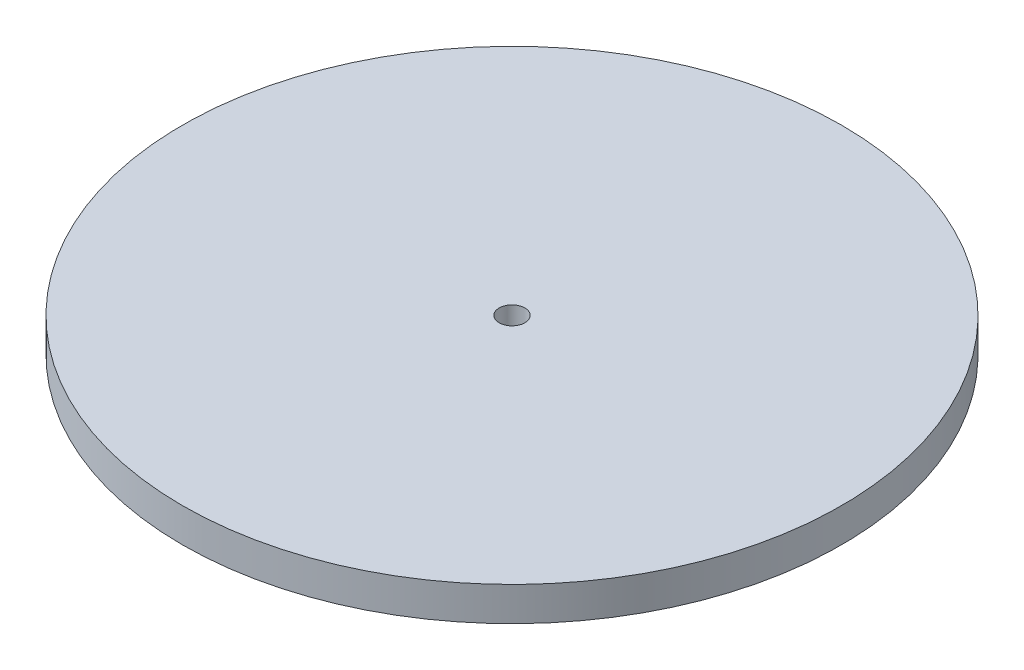
SolidWorks part; units mm, degrees
ref_plane "Front Plane" through (0, 0, 0) normal (0, 0, 1) x (1, 0, 0)
ref_plane "Top Plane" through (0, 0, 0) normal (0, 1, 0) x (1, 0, 0)
ref_plane "Right Plane" through (0, 0, 0) normal (1, 0, 0) x (0, 0, -1)
sketch "Sketch1" plane through (0, 0, 0) normal (0, 1, 0) x (1, 0, 0)
  circle A0 centre (0, 0) radius 64
  circle A1 centre (0, 0) radius 2.5
  dimension "D1" = 5
  dimension "D2" = 128
extrude "Prop disc" add sketch "Sketch1" along normal blind 6.6
